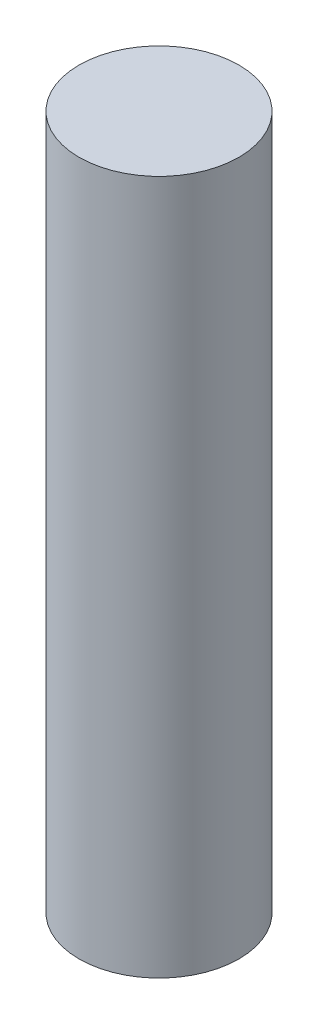
SolidWorks part; units mm, degrees
ref_plane "前视基准面" through (0, 0, 0) normal (0, 0, 1) x (1, 0, 0)
ref_plane "上视基准面" through (0, 0, 0) normal (0, 1, 0) x (1, 0, 0)
ref_plane "右视基准面" through (0, 0, 0) normal (1, 0, 0) x (0, 0, -1)
sketch "草图1" plane through (0, 0, 0) normal (0, 1, 0) x (1, 0, 0)
  circle A0 centre (0, 0) radius 4.49
extrude "凸台-拉伸1" add sketch "草图1" along normal blind 39
